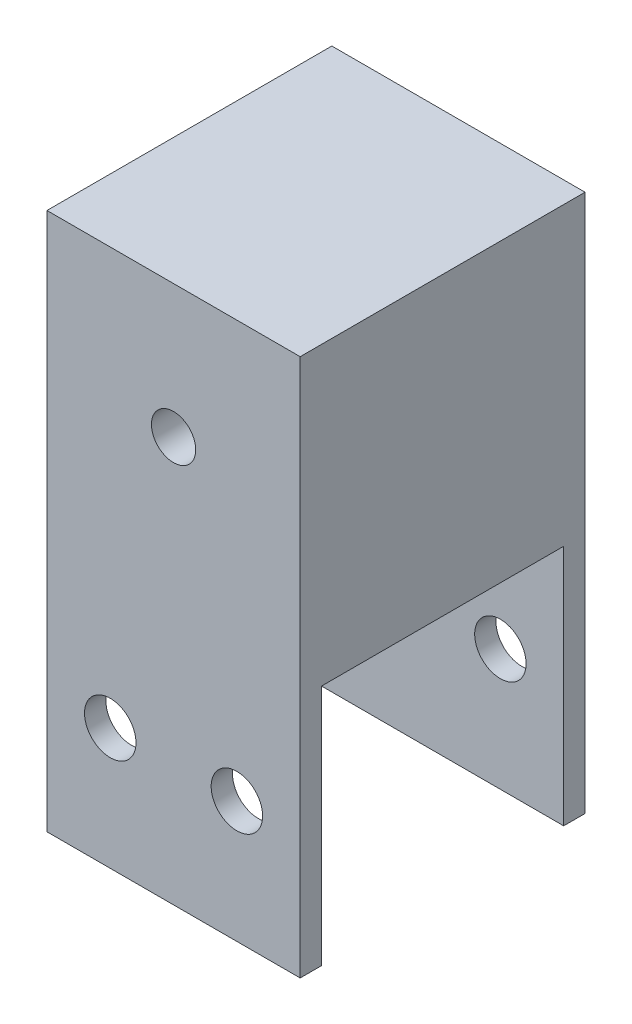
SolidWorks part; units mm, degrees
ref_plane "Plan de face" through (0, 0, 0) normal (0, 0, 1) x (1, 0, 0)
ref_plane "Plan de dessus" through (0, 0, 0) normal (0, 1, 0) x (1, 0, 0)
ref_plane "Plan de droite" through (0, 0, 0) normal (1, 0, 0) x (0, 0, -1)
sketch "Esquisse1" plane through (0, 0, 0) normal (0, 0, 1) x (1, 0, 0)
  line L1 (0, 0) -> (40, 0)
  line L2 (0, 0) -> (0, 85)
  line L3 (0, 85) -> (40, 85)
  line L4 (40, 0) -> (40, 85)
  dimension "D1" = 40
  dimension "D2" = 85
extrude "Boss.-Extru.1" add sketch "Esquisse1" along normal blind 45
sketch "Esquisse2" plane through (40, 0, 0) normal (1, 0, 0) x (0, 0, -1)
  line L0 (-45, 0) -> (0, 0) construction
  line L1 (-41.625, 0) -> (-3.375, 0)
  line L2 (-41.625, 0) -> (-41.625, 38.25)
  line L3 (-41.625, 38.25) -> (-3.375, 38.25)
  line L4 (-3.375, 0) -> (-3.375, 38.25)
  dimension "D1" = 3.375
  dimension "D2" = 3.375
  dimension "D3" = 38.25
  dimension "D4" = 38.25
extrude "Enlèv. mat.-Extru.1" cut sketch "Esquisse2" against normal through all
sketch "Esquisse3" plane through (0, 0, 41.625) normal (0, 0, -1) x (-1, 0, 0)
  line L2 (0, 38.25) -> (-40, 38.25) construction
  circle A0 centre (-30, 19.2) radius 4.065
  circle A1 centre (-10, 19.2) radius 4.065
  dimension "D2" = 8.13
  dimension "D1" = 19.05
  dimension "D3" = 20
  dimension "D4" = 10
extrude "Enlèv. mat.-Extru.2" cut sketch "Esquisse3" against normal through all both and the other way through all
sketch "Esquisse6" plane through (0, 0, 0) normal (0, 0, 1) x (1, 0, 0)
  line L0 (40, 85) -> (0, 85) construction
  circle A0 centre (20, 64) radius 6.675
  point P8 (20, 85)
  dimension "D1" = 13.35
  dimension "D2" = 21
extrude "Boss.-Extru.2" add sketch "Esquisse6" against normal blind 5
sketch "Esquisse4" plane through (0, 0, 0) normal (0, 0, -1) x (-1, 0, 0)
  line L0 (-40, 85) -> (0, 85) construction
  circle A0 centre (-20, 64) radius 3.5
  point P6 (-20, 85)
  dimension "D1" = 21
  dimension "D2" = 7
extrude "Enlèv. mat.-Extru.4" cut sketch "Esquisse4" against normal through all both and the other way through all contours A0
